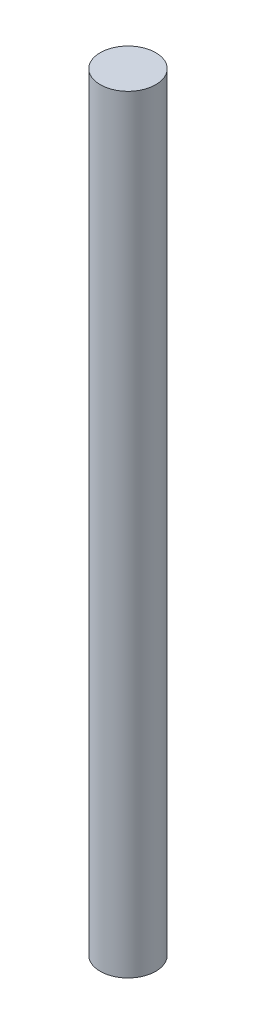
SolidWorks part; units mm, degrees
ref_plane "前视基准面" through (0, 0, 0) normal (0, 0, 1) x (1, 0, 0)
ref_plane "上视基准面" through (0, 0, 0) normal (0, 1, 0) x (1, 0, 0)
ref_plane "右视基准面" through (0, 0, 0) normal (1, 0, 0) x (0, 0, -1)
other "Configuration Table"
sketch "草图1" plane through (0, 0, 0) normal (0, 1, 0) x (1, 0, 0)
  circle A0 centre (0, 0) radius 1.5
  dimension "D1" = 3
extrude "凸台-拉伸1" add sketch "草图1" along normal blind 41.5
